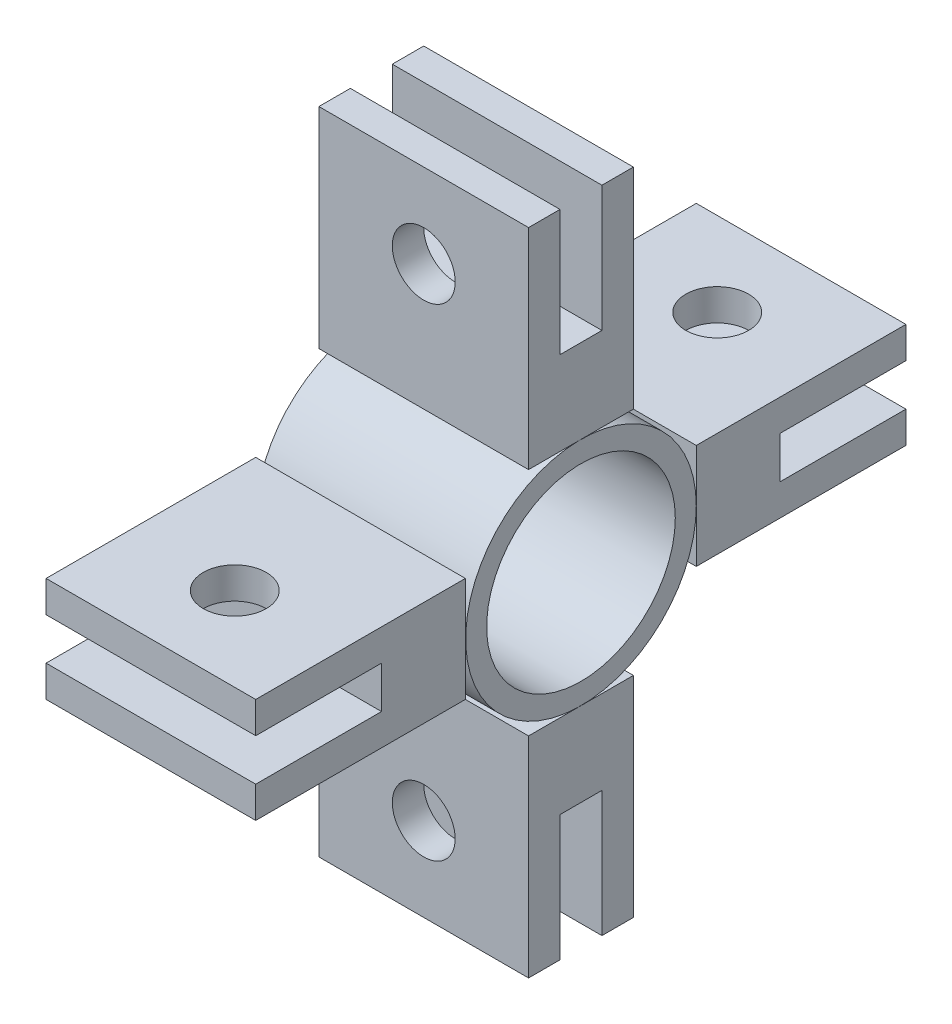
SolidWorks part; units mm, degrees
ref_plane "前视基准面" through (0, 0, 0) normal (0, 0, 1) x (1, 0, 0)
ref_plane "上视基准面" through (0, 0, 0) normal (0, 1, 0) x (1, 0, 0)
ref_plane "右视基准面" through (0, 0, 0) normal (1, 0, 0) x (0, 0, -1)
sketch "草图1" plane through (0, 0, 0) normal (1, 0, 0) x (0, 0, -1)
  circle A0 centre (0, 0) radius 55
  dimension "D1" = 110
extrude "凸台-拉伸1" add sketch "草图1" along normal blind 100
shell "抽壳1" thickness 10
ref_plane "基准面4" through (0, 0, -55) normal (0, 0, -1) x (-1, 0, 0)
sketch "草图2" plane through (0, 0, -55) normal (0, 0, -1) x (-1, 0, 0)
  line L0 (0, -55) -> (0, 55) construction
  line L1 (-100, 25) -> (0, 25)
  line L2 (-100, 25) -> (-100, -25)
  line L3 (-100, -25) -> (0, -25)
  line L4 (0, 25) -> (0, -25)
  line L5 (-100, 25) -> (0, -25) construction
  line L6 (-100, -25) -> (0, 25) construction
  point P0 (-50, 0)
  point P7 (-50, 0)
  point P8 (-50, 0)
  dimension "D1" = 100
  dimension "D2" = 50
extrude "凸台-拉伸2" add sketch "草图2" along normal blind 100 separate body
sketch "草图3" plane through (0, 0, -155) normal (0, 0, -1) x (-1, 0, 0)
  line L0 (0, 25) -> (-100, 25) construction
  line L1 (-105.1039, 10) -> (4.8961, 10)
  line L2 (-105.1039, 10) -> (-105.1039, -10)
  line L3 (-105.1039, -10) -> (4.8961, -10)
  line L4 (4.8961, 10) -> (4.8961, -10)
  line L5 (-105.1039, 10) -> (4.8961, -10) construction
  line L6 (-105.1039, -10) -> (4.8961, 10) construction
  point P0 (-50.1039, 0)
  point P5 (-50.2077, 1.5061)
  point P8 (-50.1039, 0)
  dimension "D1" = 110
  dimension "D2" = 20
  dimension "D3" = 25
extrude "切除-拉伸5" cut sketch "草图3" against normal blind 60
sketch "草图4" plane through (0, -25, 0) normal (0, -1, 0) x (1, 0, 0)
  line L0 (100, -155) -> (100, -55) construction
  line L1 (100, -155) -> (0, -155) construction
  circle A0 centre (50, -115) radius 15
  dimension "D1" = 30
  dimension "D2" = 50
  dimension "D3" = 40
extrude "切除-拉伸6" cut sketch "草图4" against normal blind 60
ref_plane "基准面5" through (0, 0, 55) normal (0, 0, 1) x (1, 0, 0)
sketch "草图6" plane through (0, 0, 55) normal (0, 0, 1) x (1, 0, 0)
  line L1 (-0.1408, 25) -> (99.8592, 25)
  line L2 (-0.1408, 25) -> (-0.1408, -25)
  line L3 (-0.1408, -25) -> (99.8592, -25)
  line L4 (99.8592, 25) -> (99.8592, -25)
  line L5 (-0.1408, 25) -> (99.8592, -25) construction
  line L6 (-0.1408, -25) -> (99.8592, 25) construction
  point P0 (49.8592, 0)
  point P5 (49.7519, -4.8097)
  point P6 (49.8592, -1.911)
  point P7 (49.8592, 0)
  dimension "D1" = 100
  dimension "D2" = 50
extrude "凸台-拉伸4" add sketch "草图6" along normal blind 100 separate body
sketch "草图7" plane through (0, 0, 155) normal (0, 0, 1) x (1, 0, 0)
  line L0 (100, -55) -> (100, 55) construction
  line L1 (-10, 10) -> (100, 10)
  line L2 (-10, 10) -> (-10, -10)
  line L3 (-10, -10) -> (100, -10)
  line L4 (100, 10) -> (100, -10)
  line L5 (-10, 10) -> (100, -10) construction
  line L6 (-10, -10) -> (100, 10) construction
  point P0 (45, 0)
  point P7 (50, 0)
  point P8 (45, 0)
  point P9 (45, 0)
  point P10 (45, 0)
  point P11 (45, 0)
  point P12 (45, 0)
  point P13 (45, 0)
  point P14 (45, 0)
  dimension "D1" = 110
  dimension "D2" = 20
extrude "切除-拉伸8" cut sketch "草图7" against normal blind 60
sketch "草图8" plane through (0, -25, 0) normal (0, -1, 0) x (1, 0, 0)
  line L0 (-0.1408, 155) -> (99.8592, 155) construction
  line L1 (99.8592, 155) -> (99.8592, 55) construction
  circle A0 centre (49.8592, 115) radius 15
  dimension "D1" = 30
  dimension "D3" = 50
  dimension "D2" = 40
extrude "切除-拉伸9" cut sketch "草图8" against normal blind 60
ref_plane "基准面6" through (0, -55, 0) normal (0, -1, 0) x (-1, 0, 0)
sketch "草图9" plane through (0, -55, 0) normal (0, -1, 0) x (-1, 0, 0)
  line L0 (0, -55) -> (0, 55) construction
  line L1 (-100, 25) -> (0, 25)
  line L2 (-100, 25) -> (-100, -25)
  line L3 (-100, -25) -> (0, -25)
  line L4 (0, 25) -> (0, -25)
  line L5 (-100, 25) -> (0, -25) construction
  line L6 (-100, -25) -> (0, 25) construction
  point P0 (-50, 0)
  point P7 (-50, 0)
  dimension "D1" = 100
  dimension "D2" = 50
extrude "凸台-拉伸5" add sketch "草图9" along normal blind 100 separate body
sketch "草图10" plane through (0, -155, 0) normal (0, -1, 0) x (1, 0, 0)
  line L0 (100, -25) -> (100, 25) construction
  line L1 (-4.304, 10) -> (100, 10)
  line L2 (-4.304, 10) -> (-4.304, -10)
  line L3 (-4.304, -10) -> (100, -10)
  line L4 (100, 10) -> (100, -10)
  line L5 (-4.304, 10) -> (100, -10) construction
  line L6 (-4.304, -10) -> (100, 10) construction
  point P0 (47.848, 0)
  point P7 (47.848, 0)
  dimension "D1" = 104.304
  dimension "D2" = 20
extrude "切除-拉伸11" cut sketch "草图10" against normal blind 60
sketch "草图11" plane through (0, 0, 25) normal (0, 0, 1) x (1, 0, 0)
  line L0 (100, -155) -> (100, -55) construction
  line L1 (100, -155) -> (0, -155) construction
  circle A0 centre (50, -115) radius 15
  point P4 (0, 0)
  dimension "D1" = 30
  dimension "D2" = 50
  dimension "D3" = 40
extrude "切除-拉伸12" cut sketch "草图11" against normal blind 60
ref_plane "基准面7" through (0, 55, 0) normal (0, 1, 0) x (1, 0, 0)
sketch "草图12" plane through (0, 55, 0) normal (0, 1, 0) x (1, 0, 0)
  line L0 (100, -55) -> (100, 55) construction
  line L1 (0, 25) -> (100, 25)
  line L2 (0, 25) -> (0, -25)
  line L3 (0, -25) -> (100, -25)
  line L4 (100, 25) -> (100, -25)
  line L5 (0, 25) -> (100, -25) construction
  line L6 (0, -25) -> (100, 25) construction
  point P0 (50, 0)
  point P7 (50, 0)
  dimension "D1" = 100
  dimension "D2" = 50
extrude "凸台-拉伸6" add sketch "草图12" along normal blind 100 separate body
sketch "草图13" plane through (0, 155, 0) normal (0, 1, 0) x (1, 0, 0)
  line L1 (-18.6814, 10) -> (123.4255, 10)
  line L2 (-18.6814, 10) -> (-18.6814, -10)
  line L3 (-18.6814, -10) -> (123.4255, -10)
  line L4 (123.4255, 10) -> (123.4255, -10)
  line L5 (-18.6814, 10) -> (123.4255, -10) construction
  line L6 (-18.6814, -10) -> (123.4255, 10) construction
  point P0 (52.372, 0)
  point P5 (52.372, 0)
  dimension "D1" = 20
extrude "切除-拉伸13" cut sketch "草图13" against normal blind 60
sketch "草图14" plane through (0, 0, 25) normal (0, 0, 1) x (1, 0, 0)
  line L0 (0, 155) -> (100, 155) construction
  line L1 (0, 155) -> (0, 55) construction
  circle A0 centre (50, 115) radius 15
  dimension "D1" = 30
  dimension "D2" = 40
  dimension "D3" = 50
extrude "切除-拉伸14" cut sketch "草图14" against normal blind 60
